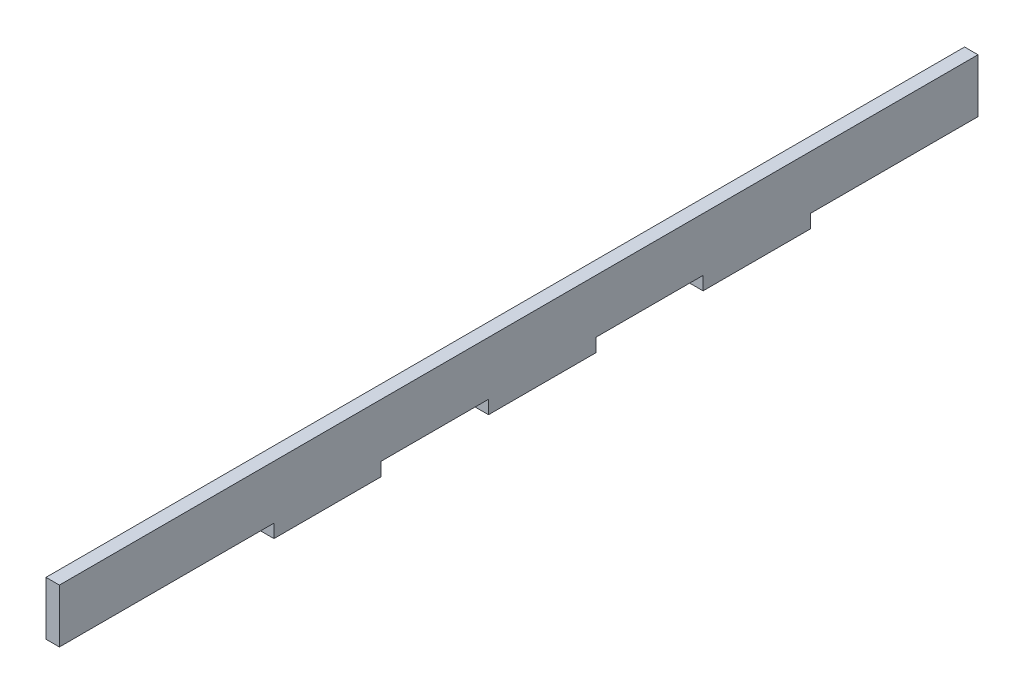
SolidWorks part; units mm, degrees
ref_plane "Front Plane" through (0, 0, 0) normal (0, 0, 1) x (1, 0, 0)
ref_plane "Top Plane" through (0, 0, 0) normal (0, 1, 0) x (1, 0, 0)
ref_plane "Right Plane" through (0, 0, 0) normal (1, 0, 0) x (0, 0, -1)
sketch "Sketch1" plane through (0, 0, 0) normal (1, 0, 0) x (0, 0, -1)
  line L7 (3.131, 0) -> (438.131, 0)
  line L8 (3.131, 0) -> (3.131, 31.75)
  line L9 (3.131, 31.75) -> (438.131, 31.75)
  line L10 (438.131, 0) -> (438.131, 31.75)
  dimension "D1" = 31.75
  dimension "D2" = 435
extrude "Boss-Extrude1" add sketch "Sketch1" along normal blind 6.35
sketch "Sketch2" plane through (0, 0, 0) normal (-1, 0, 0) x (0, 0, 1)
  line L1 (-3.131, 0) -> (-104.731, 0)
  line L2 (-3.131, 0) -> (-3.131, 6.35)
  line L3 (-3.131, 6.35) -> (-104.731, 6.35)
  line L4 (-104.731, 0) -> (-104.731, 6.35)
  dimension "D1" = 101.6
  dimension "D2" = 6.35
extrude "Cut-Extrude1" cut sketch "Sketch2" against normal up to next
sketch "Sketch3" plane through (0, 0, 0) normal (-1, 0, 0) x (0, 0, 1)
  line L0 (-104.731, 0) -> (-438.131, 0) construction
  line L1 (-155.531, 0) -> (-206.331, 0)
  line L2 (-155.531, 0) -> (-155.531, 6.35)
  line L3 (-155.531, 6.35) -> (-206.331, 6.35)
  line L4 (-206.331, 0) -> (-206.331, 6.35)
  line L5 (-104.731, 6.35) -> (-104.731, 0) construction
  line L7 (-257.131, 0) -> (-307.931, 0)
  line L8 (-257.131, 0) -> (-257.131, 6.35)
  line L9 (-257.131, 6.35) -> (-307.931, 6.35)
  line L10 (-307.931, 0) -> (-307.931, 6.35)
  line L11 (-438.131, 0) -> (-358.731, 0)
  line L12 (-438.131, 0) -> (-438.131, 6.35)
  line L13 (-438.131, 6.35) -> (-358.731, 6.35)
  line L14 (-358.731, 0) -> (-358.731, 6.35)
  point P16 (-307.931, 3.175)
  dimension "D1" = 6.35
  dimension "D2" = 50.8
  dimension "D3" = 50.8
  dimension "D4" = 50.8
  dimension "D5" = 50.8
extrude "Cut-Extrude2" cut sketch "Sketch3" against normal up to next
